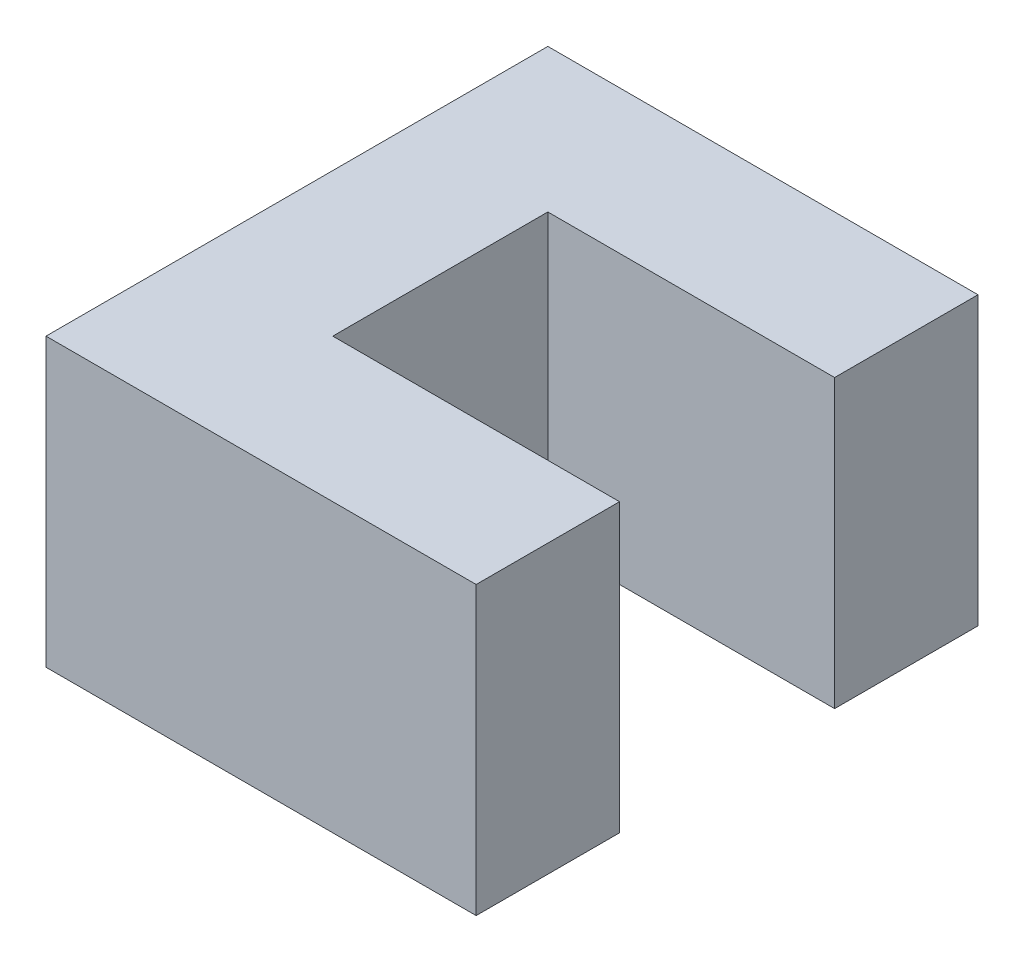
SolidWorks part; units mm, degrees
ref_plane "Přední rovina" through (0, 0, 0) normal (0, 0, 1) x (1, 0, 0)
ref_plane "Horní rovina" through (0, 0, 0) normal (0, 1, 0) x (1, 0, 0)
ref_plane "Pravá rovina" through (0, 0, 0) normal (1, 0, 0) x (0, 0, -1)
sketch "Sketch1" plane through (0, 0, 0) normal (0, 1, 0) x (1, 0, 0)
  line L0 (0, 0) -> (0, -35)
  line L1 (0, -35) -> (30, -35)
  line L2 (30, -35) -> (30, -25)
  line L3 (30, -25) -> (10, -25)
  line L4 (10, -25) -> (10, -10)
  line L5 (10, -10) -> (30, -10)
  line L6 (30, -10) -> (30, 0)
  line L7 (30, 0) -> (0, 0)
  dimension "D1" = 10
  dimension "D2" = 10
  dimension "D3" = 15
  dimension "D4" = 10
  dimension "D5" = 20
extrude "Boss-Extrude1" add sketch "Sketch1" along normal blind 20
equation "\"H\"= 15"
equation "\"D3@Sketch1\"=\"H\""
equation "\"L\"= 20"
equation "\"D5@Sketch1\"=\"L\""
